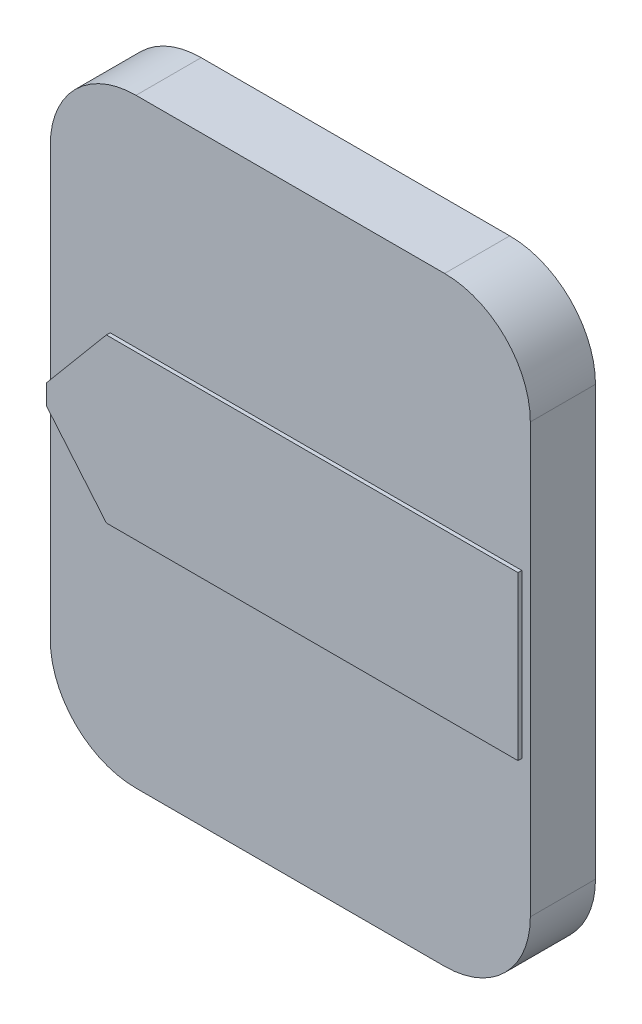
SolidWorks part; units mm, degrees
ref_plane "Front Plane" through (0, 0, 0) normal (0, 0, 1) x (1, 0, 0)
ref_plane "Top Plane" through (0, 0, 0) normal (0, 1, 0) x (1, 0, 0)
ref_plane "Right Plane" through (0, 0, 0) normal (1, 0, 0) x (0, 0, -1)
sketch "Sketch1" plane through (0, 0, 0) normal (0, 0, 1) x (1, 0, 0)
  line L0 (2.8, 3.5) -> (0, 3.5)
  line L1 (0, 3.5) -> (0, 0)
  line L2 (0, 0) -> (2.8, 0)
  line L3 (2.8, 0) -> (2.8, 3.5)
extrude "Boss-Extrude1" add sketch "Sketch1" against normal blind 0.38
fillet "Fillet1" radius 0.5 4 edges at (2.8, 3.5, -0.19) (2.8, 0, -0.19) (0, 0, -0.19) (0, 3.5, -0.19)
sketch "Sketch2" plane through (0, 0, 0) normal (0, 0, 1) x (1, 0, 0)
  line L0 (0, 1.6911) -> (0, 1.8089)
  line L1 (0, 1.8089) -> (0.3492, 2.225)
  line L2 (0.3492, 2.225) -> (2.75, 2.225)
  line L3 (2.75, 2.225) -> (2.75, 1.275)
  line L4 (2.75, 1.275) -> (0.3492, 1.275)
  line L5 (0.3492, 1.275) -> (0, 1.6911)
extrude "Boss-Extrude2" add sketch "Sketch2" along normal blind 0.022
sketch "Sketch3" plane through (0, 0, -0.38) normal (0, 0, -1) x (-1, 0, 0)
  line L16 (-2.7, 3) -> (-2.7, 0.5)
  line L17 (-2.3, 0.1) -> (-0.5, 0.1)
  line L18 (-0.1, 0.5) -> (-0.1, 3)
  line L19 (-0.5, 3.4) -> (-2.3, 3.4)
  line L20 (-2.7, 3) -> (-2.7, 0.5)
  line L21 (-2.3, 0.1) -> (-0.5, 0.1)
  line L22 (-0.1, 0.5) -> (-0.1, 3)
  line L23 (-0.5, 3.4) -> (-2.3, 3.4)
  arc A16 (-2.7, 0.5) -> (-2.3, 0.1) centre (-2.3, 0.5) ccw
  arc A17 (-0.5, 0.1) -> (-0.1, 0.5) centre (-0.5, 0.5) ccw
  arc A18 (-0.1, 3) -> (-0.5, 3.4) centre (-0.5, 3) ccw
  arc A19 (-2.3, 3.4) -> (-2.7, 3) centre (-2.3, 3) ccw
  arc A20 (-2.7, 0.5) -> (-2.3, 0.1) centre (-2.3, 0.5) ccw
  arc A21 (-0.5, 0.1) -> (-0.1, 0.5) centre (-0.5, 0.5) ccw
  arc A22 (-0.1, 3) -> (-0.5, 3.4) centre (-0.5, 3) ccw
  arc A23 (-2.3, 3.4) -> (-2.7, 3) centre (-2.3, 3) ccw
  dimension "D1" = 0.1
extrude "Boss-Extrude3" add sketch "Sketch3" along normal blind 0.022
